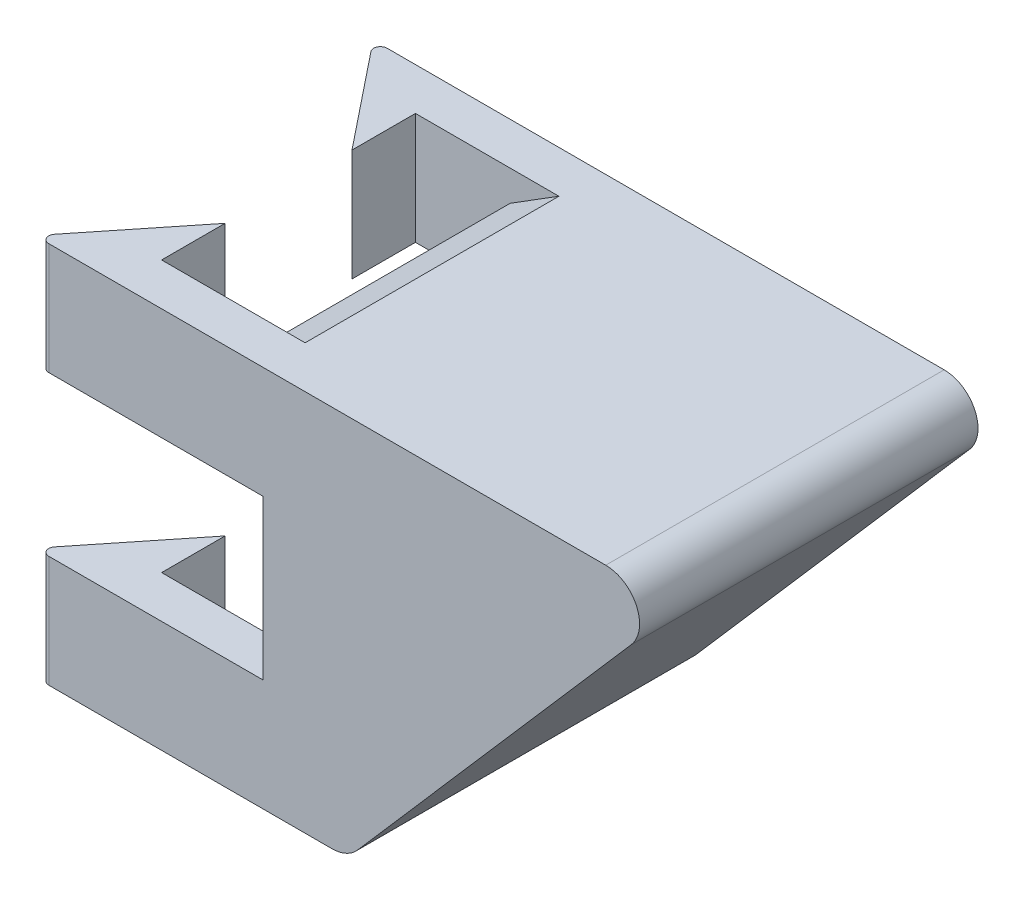
SolidWorks part; units mm, degrees
ref_plane "Front Plane" through (0, 0, 0) normal (0, 0, 1) x (1, 0, 0)
ref_plane "Top Plane" through (0, 0, 0) normal (0, 1, 0) x (1, 0, 0)
ref_plane "Right Plane" through (0, 0, 0) normal (1, 0, 0) x (0, 0, -1)
sketch "Sketch1" plane through (0, 0, 0) normal (0, 0, 1) x (1, 0, 0)
  line L0 (3.5547, 0.4366) -> (13.8267, 12.2476)
  line L1 (0, 0) -> (2.5964, 0)
  line L2 (0, 0) -> (0, 14.351)
  line L6 (0, 14.351) -> (12.8685, 14.351)
  arc A0 (2.5964, 0) -> (3.5547, 0.4366) centre (2.5964, 1.27) ccw
  arc A1 (13.8267, 12.2476) -> (12.8685, 14.351) centre (12.8685, 13.081) ccw
  point P7 (3.175, 0)
  dimension "D3" = 1.27
  dimension "D1" = 14.351
  dimension "D2" = 3.175
  dimension "D4" = 12.8685
extrude "Boss-Extrude1" add sketch "Sketch1" along normal blind 12.7
sketch "Sketch2" plane through (0, 0, 0) normal (-1, 0, 0) x (0, 0, 1)
  line L0 (12.7, 0) -> (0, 0) construction
  line L1 (0, 14.351) -> (1.5875, 14.351)
  line L2 (0, 14.351) -> (0, 10.16)
  line L3 (0, 0) -> (1.5875, 0)
  line L4 (1.5875, 14.351) -> (1.5875, 10.16)
  line L5 (6.35, 14.351) -> (6.35, 6.985) construction
  line L6 (12.7, 14.351) -> (0, 14.351) construction
  line L8 (0, 4.191) -> (1.5875, 4.191)
  line L10 (0, 10.16) -> (1.5875, 10.16)
  line L12 (12.7, 4.191) -> (12.7, 0)
  line L13 (12.7, 0) -> (11.1125, 0)
  line L14 (1.5875, 4.191) -> (1.5875, 0)
  line L15 (0, 4.191) -> (0, 0)
  line L16 (11.1125, 4.191) -> (11.1125, 0)
  line L17 (12.7, 4.191) -> (11.1125, 4.191)
  line L18 (12.7, 14.351) -> (11.1125, 14.351)
  line L19 (11.1125, 14.351) -> (11.1125, 10.16)
  line L20 (12.7, 10.16) -> (11.1125, 10.16)
  line L21 (12.7, 14.351) -> (12.7, 10.16)
  point P11 (6.35, 6.985)
  dimension "D1" = 1.5875
  dimension "D2" = 4.191
  dimension "D3" = 4.191
sketch "Sketch3" plane through (0, 0, 0) normal (-1, 0, 0) x (0, 0, 1)
  line L0 (1.5875, 9.017) -> (1.5875, 5.334)
  line L5 (1.5875, 9.017) -> (11.1125, 9.017)
  line L6 (11.1125, 14.351) -> (11.1125, 10.16) construction
  line L7 (1.5875, 14.351) -> (11.1125, 14.351)
  line L8 (1.5875, 14.351) -> (1.5875, 10.668)
  line L9 (1.5875, 10.668) -> (11.1125, 10.668)
  line L10 (11.1125, 14.351) -> (11.1125, 10.668)
  line L11 (11.1125, 9.017) -> (11.1125, 5.334)
  line L12 (1.5875, 5.334) -> (11.1125, 5.334)
  line L13 (1.5875, 3.683) -> (1.5875, 0)
  line L14 (1.5875, 3.683) -> (11.1125, 3.683)
  line L15 (11.1125, 3.683) -> (11.1125, 0)
  line L16 (1.5875, 0) -> (11.1125, 0)
  line L17 (1.5875, 14.351) -> (1.5875, 9.017) construction
  dimension "D1" = 3.683
  dimension "D3" = 5.334
  dimension "D4" = 14.351
  dimension "D5" = 1.651
  dimension "D2" = 3
extrude "Boss-Extrude2" add sketch "Sketch3" along normal blind 1.2573 draft 24.44
extrude "Boss-Extrude3" add sketch "Sketch2" along normal blind 5.3848
sketch "Sketch4" plane through (-5.3848, 0, 0) normal (-1, 0, 0) x (0, 0, 1)
  line L0 (1.5875, 14.351) -> (0, 14.351) construction
  line L1 (0, 14.351) -> (3.9688, 14.351)
  line L2 (0, 14.351) -> (0, 10.16)
  line L3 (0, 10.16) -> (3.9688, 10.16)
  line L4 (3.9688, 14.351) -> (3.9688, 10.16)
  line L7 (6.35, 8.4456) -> (6.35, 5.9054) construction
  line L8 (10.5411, 8.4456) -> (2.1589, 8.4456) construction
  line L9 (2.1589, 5.9054) -> (10.5411, 5.9054) construction
  line L10 (10.5411, 7.1755) -> (2.1589, 7.1755) construction
  line L11 (10.5411, 5.9054) -> (10.5411, 8.4456) construction
  line L12 (2.1589, 8.4456) -> (2.1589, 5.9054) construction
  line L14 (12.7, 10.16) -> (8.7313, 10.16)
  line L15 (8.7313, 14.351) -> (8.7313, 10.16)
  line L16 (12.7, 14.351) -> (8.7313, 14.351)
  line L17 (12.7, 14.351) -> (12.7, 10.16)
  line L18 (12.7, 0) -> (12.7, 4.191)
  line L19 (12.7, 0) -> (8.7313, 0)
  line L20 (8.7313, 0) -> (8.7313, 4.191)
  line L21 (12.7, 4.191) -> (8.7313, 4.191)
  line L22 (0, 4.191) -> (3.9688, 4.191)
  line L23 (3.9688, 0) -> (3.9688, 4.191)
  line L24 (0, 0) -> (3.9688, 0)
  line L25 (0, 0) -> (0, 4.191)
  dimension "D1" = 4.191
  dimension "D2" = 3.9688
extrude "Boss-Extrude4" add sketch "Sketch4" along normal blind 3.175
sketch "Sketch5" plane through (0, 0, 0) normal (0, -1, 0) x (1, 0, 0)
  line L0 (-5.3848, 3.9688) -> (-8.5598, 0)
  line L1 (-8.5598, 0) -> (-8.5598, 3.9688)
  line L2 (-8.5598, 3.9688) -> (-5.3848, 3.9688)
  line L3 (2.5964, 6.35) -> (-11.6759, 6.35) construction
  line L4 (2.5964, 12.7) -> (2.5964, 0) construction
  line L5 (-8.5598, 12.7) -> (-8.5598, 8.7312)
  line L6 (-5.3848, 8.7312) -> (-8.5598, 12.7)
  line L7 (-8.5598, 8.7312) -> (-5.3848, 8.7312)
extrude "Cut-Extrude1" cut sketch "Sketch5" against normal up to surface (14.351 mm away)
fillet "Fillet1" radius 0.254 4 edges at (-8.5598, 12.2555, 12.7) (-8.5598, 2.0955, 12.7) (-8.5598, 12.2555, 0) (-8.5598, 2.0955, 0)
